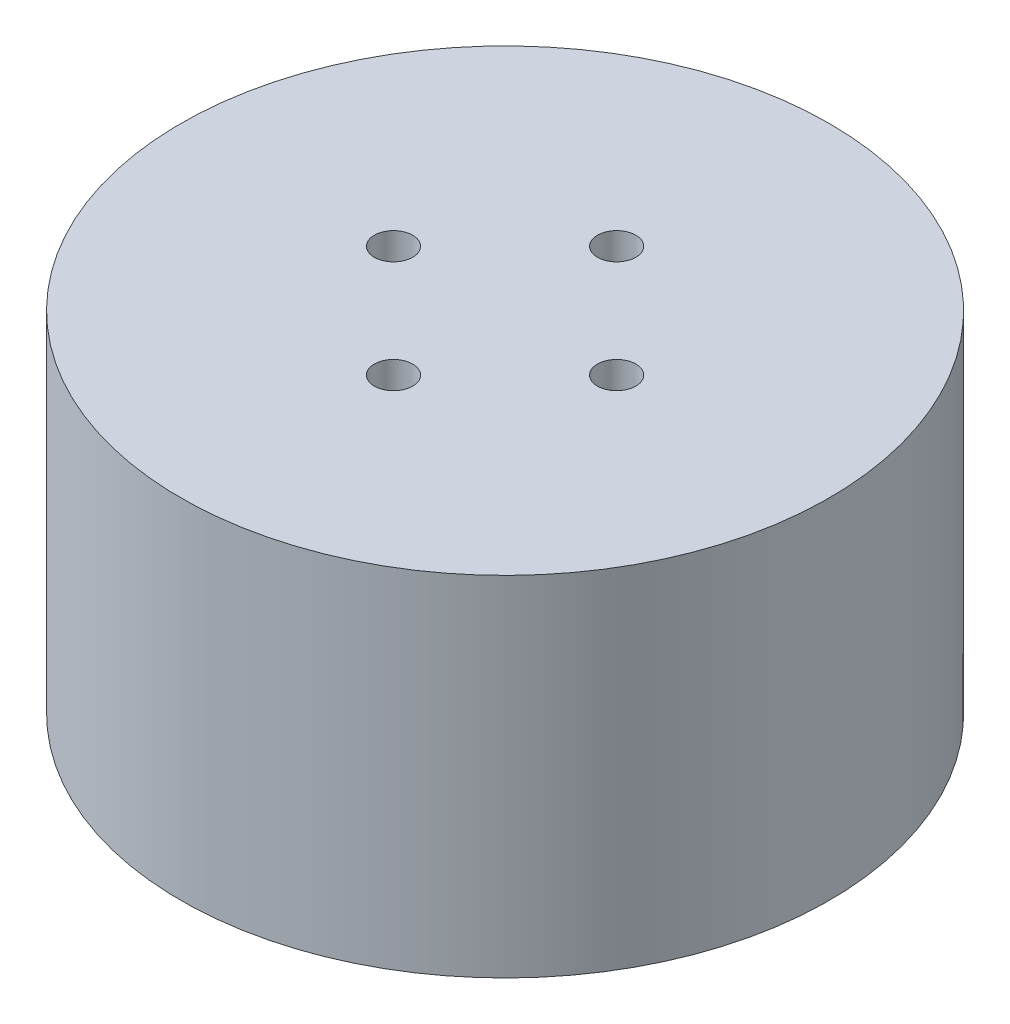
SolidWorks part; units mm, degrees
ref_plane "Plan de face" through (0, 0, 0) normal (0, 0, 1) x (1, 0, 0)
ref_plane "Plan de dessus" through (0, 0, 0) normal (0, 1, 0) x (1, 0, 0)
ref_plane "Plan de droite" through (0, 0, 0) normal (1, 0, 0) x (0, 0, -1)
sketch "Esquisse1" plane through (0, 0, 0) normal (0, 1, 0) x (1, 0, 0)
  circle A0 centre (0, 0) radius 47.75
  dimension "D1" = 95.5
extrude "Boss.-Extru.1" add sketch "Esquisse1" along normal blind 50
sketch "Esquisse2" plane through (0, 0, 0) normal (0, -1, 0) x (-1, 0, 0)
  circle A0 centre (0, 0) radius 26
extrude "Enlèv. mat.-Extru.1" cut sketch "Esquisse2" against normal blind 20
sketch "Esquisse3" plane through (0, 20, 0) normal (0, -1, 0) x (-1, 0, 0)
  circle A0 centre (0, 0) radius 11
  dimension "D1" = 22
extrude "Enlèv. mat.-Extru.5" cut sketch "Esquisse3" against normal blind 7.5
sketch "Esquisse4" plane through (0, 27.5, 0) normal (0, -1, 0) x (-1, 0, 0)
  circle A0 centre (0, 0) radius 5
  dimension "D1" = 10
extrude "Enlèv. mat.-Extru.6" cut sketch "Esquisse4" against normal blind 13.5
sketch "Esquisse5" plane through (0, 50, 0) normal (0, 1, 0) x (1, 0, 0)
  line L0 (-26, 0) -> (26, 0)
  line L1 (0, 26) -> (0, -26)
  circle A0 centre (0, 0) radius 26
  point P8 (-16, 0)
  point P9 (0, 16)
  point P10 (16, 0)
  point P11 (0, -16)
  dimension "D1" = 52
sketch "Esquisse11" plane through (0, 50, 0) normal (0, 1, 0) x (1, 0, 0)
  circle A0 centre (-16, 0) radius 2.75
  circle A1 centre (0, 16) radius 2.75
  circle A2 centre (16, 0) radius 2.75
  circle A3 centre (0, -16) radius 2.75
  dimension "D1" = 5.5
  dimension "D2" = 5.5
  dimension "D3" = 5.5
  dimension "D4" = 5.5
extrude "Enlèv. mat.-Extru.11" cut sketch "Esquisse11" against normal through all
ref_plane "Plan1" through (-47.75, 0, 0) normal (-1, 0, 0) x (0, 0, 1)
ref_plane "Plan2" through (47.75, 0, 0) normal (1, 0, 0) x (0, 0, -1)
sketch "Esquisse12" plane through (0, 0, 0) normal (0, -1, 0) x (1, 0, 0)
  circle A0 centre (0, 0) radius 46.5
  circle M2 centre (0, 0) radius 47.75
extrude "Enlèv. mat.-Extru.12" cut sketch "Esquisse12" against normal through all contours A0 M2
